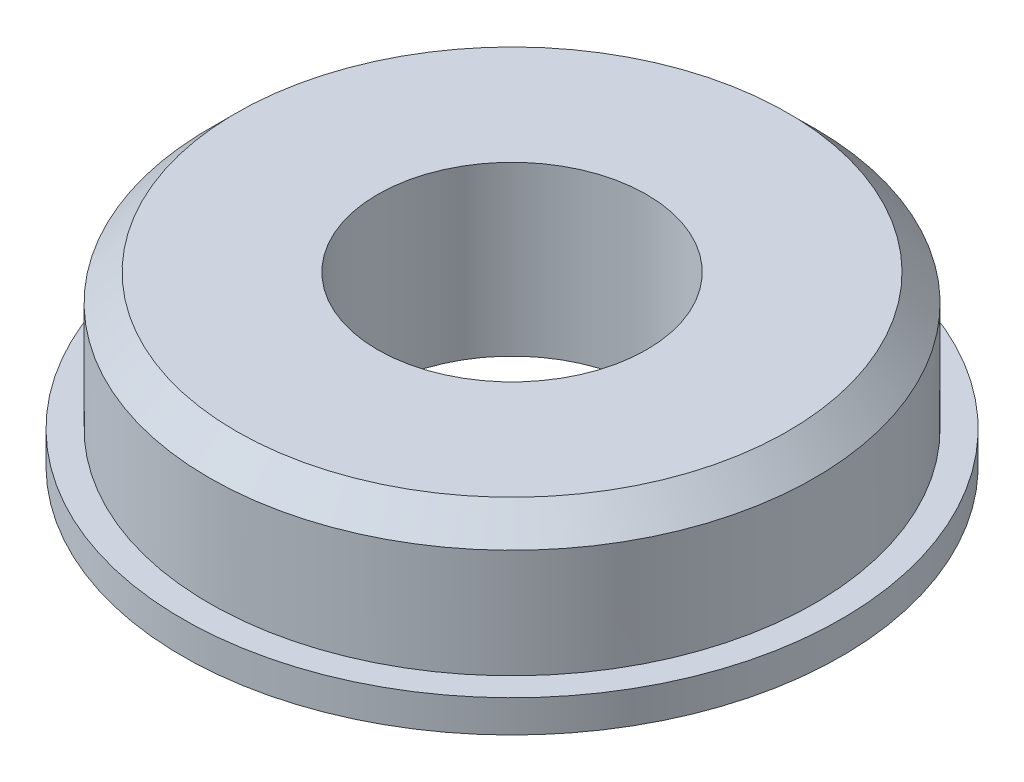
SolidWorks part; units mm, degrees
ref_plane "Front Plane" through (0, 0, 0) normal (0, 0, 1) x (1, 0, 0)
ref_plane "Top Plane" through (0, 0, 0) normal (0, 1, 0) x (1, 0, 0)
ref_plane "Right Plane" through (0, 0, 0) normal (1, 0, 0) x (0, 0, -1)
sketch "Sketch1" plane through (0, 0, 0) normal (0, 1, 0) x (1, 0, 0)
  circle A0 centre (0, 0) radius 14.2875
  circle A1 centre (0, 0) radius 6.35
  dimension "D1" = 28.575
  dimension "D2" = 12.7
extrude "Boss-Extrude1" add sketch "Sketch1" along normal blind 7.9248
chamfer "Chamfer1" distance 1.27 angle 45 1 edges at (0, 7.9248, 14.2875)
sketch "Sketch2" plane through (0, 0, 0) normal (0, -1, 0) x (1, 0, 0)
  circle A0 centre (0, 0) radius 6.35 construction
  circle A1 centre (0, 0) radius 6.35
  circle A2 centre (0, 0) radius 15.5575
  dimension "D1" = 31.115
extrude "Boss-Extrude2" add sketch "Sketch2" against normal blind 1.524
